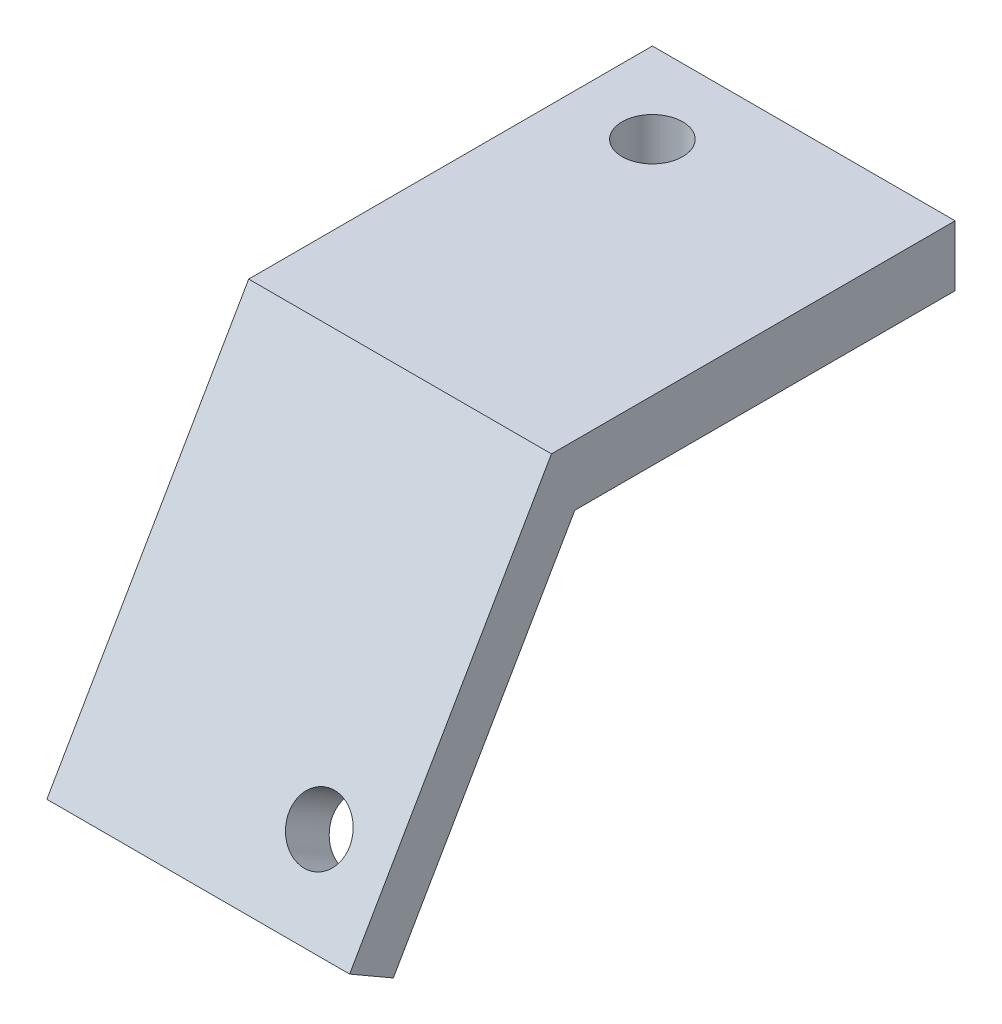
SolidWorks part; units mm, degrees
ref_plane "Front Plane" through (0, 0, 0) normal (0, 0, 1) x (1, 0, 0)
ref_plane "Top Plane" through (0, 0, 0) normal (0, 1, 0) x (1, 0, 0)
ref_plane "Right Plane" through (0, 0, 0) normal (1, 0, 0) x (0, 0, -1)
sketch "Sketch1" plane through (0, 0, 0) normal (0, 1, 0) x (1, 0, 0)
  line L1 (-7.5, -10) -> (7.5, -10)
  line L2 (-7.5, -10) -> (-7.5, 10)
  line L3 (-7.5, 10) -> (7.5, 10)
  line L4 (7.5, -10) -> (7.5, 10)
  line L5 (-7.5, -10) -> (7.5, 10) construction
  line L6 (-7.5, 10) -> (7.5, -10) construction
  circle A0 centre (-3.5, 6) radius 1.5
  point P0 (0, 0)
  dimension "D3" = 3
  dimension "D1" = 15
  dimension "D2" = 20
  dimension "D4" = 4
  dimension "D5" = 4
extrude "Boss-Extrude1" add sketch "Sketch1" along normal blind 3
ref_plane "Plane1" through (0, -2.0801, 1.201) normal (0, 0.866, -0.5) x (1, 0, 0)
sketch "Sketch2" plane through (0, -2.0801, 1.201) normal (0, 0.866, -0.5) x (1, 0, 0)
  line L0 (-7.5, -10.1603) -> (-7.5, -8.6603) construction
  line L1 (-7.5, -7.6603) -> (7.5, -7.6603)
  line L2 (-7.5, -7.6603) -> (-7.5, -10.1603)
  line L3 (-7.5, -10.1603) -> (7.5, -10.1603)
  line L4 (7.5, -7.6603) -> (7.5, -10.1603)
  line L7 (-7.5, -8.6603) -> (7.5, -8.6603) construction
  point P5 (0, 0)
  dimension "D1" = 1
extrude "Boss-Extrude2" add sketch "Sketch2" against normal blind 20
sketch "Sketch3" plane through (0, 5.0801, 8.799) normal (0, 0.5, 0.866) x (1, 0, 0)
  line L1 (-7.5, -22.4019) -> (7.5, -22.4019) construction
  circle A0 centre (4, -18.4019) radius 1.5
  ellipse E0 centre (-3.5, 5.5981) end of major axis (-2, 5.5981) minor radius 0.75 construction
  dimension "D1" = 3
  dimension "D2" = 4
  dimension "D3" = 7.5
extrude "Cut-Extrude1" cut sketch "Sketch3" against normal blind 10
